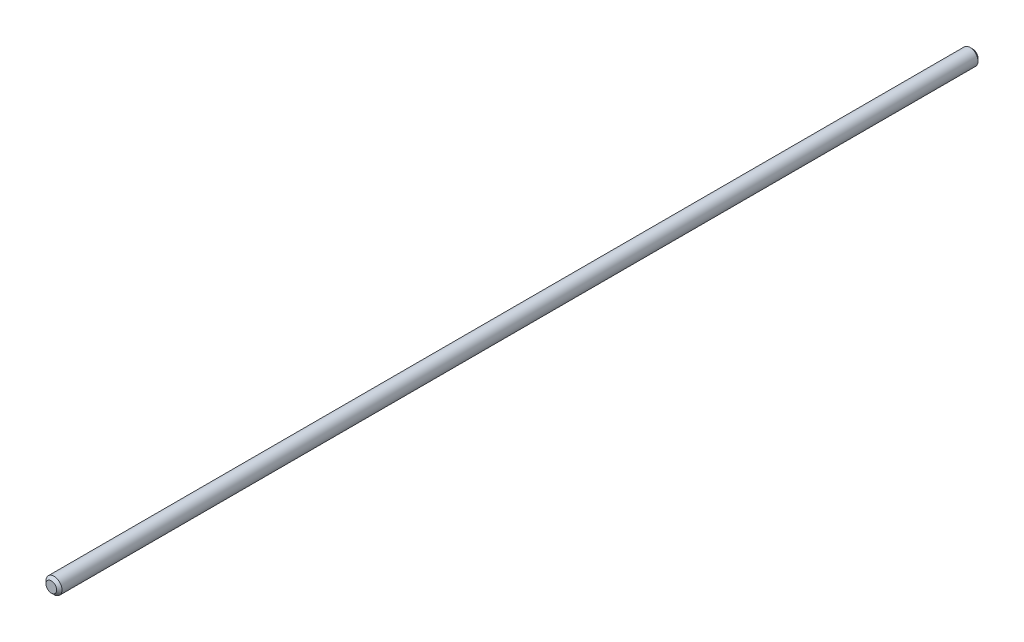
SolidWorks part; units mm, degrees
ref_plane "Спереди" through (0, 0, 0) normal (0, 0, 1) x (1, 0, 0)
ref_plane "Сверху" through (0, 0, 0) normal (0, 1, 0) x (1, 0, 0)
ref_plane "Справа" through (0, 0, 0) normal (1, 0, 0) x (0, 0, -1)
sketch "Эскиз1" plane through (0, 0, 0) normal (0, 0, 1) x (1, 0, 0)
  circle A0 centre (0, 0) radius 1.5
  dimension "D1" = 3
extrude "Бобышка-Вытянуть1" add sketch "Эскиз1" along normal blind 172.8
chamfer "Фаска1" distance 0.5 angle 45 2 edges at (1.5, 0, 172.8) (1.5, 0, 0)
